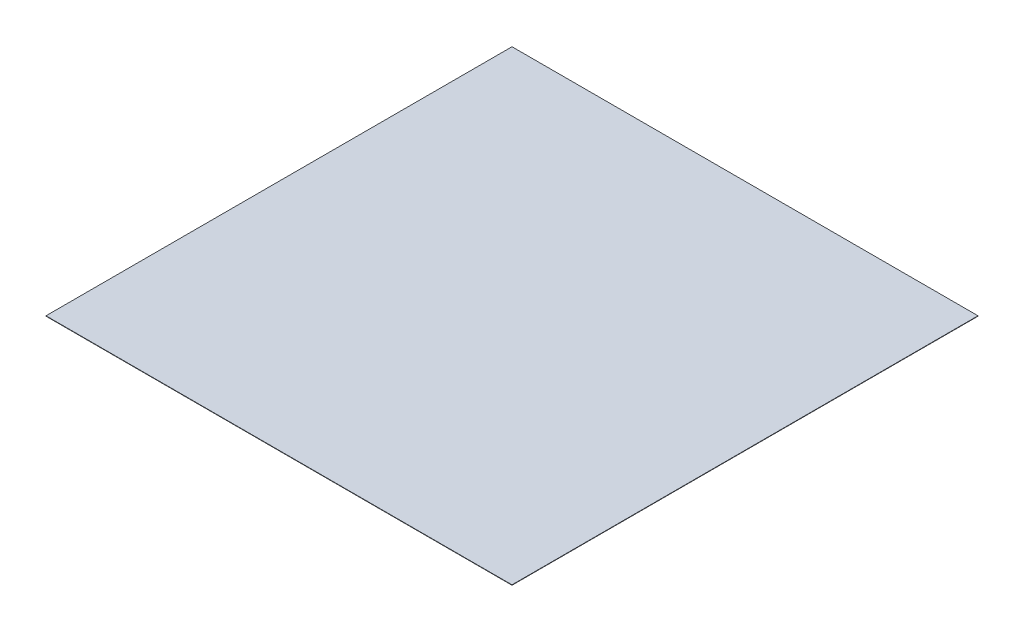
SolidWorks part; units mm, degrees
ref_plane "Front Plane" through (0, 0, 0) normal (0, 0, 1) x (1, 0, 0)
ref_plane "Top Plane" through (0, 0, 0) normal (0, 1, 0) x (1, 0, 0)
ref_plane "Right Plane" through (0, 0, 0) normal (1, 0, 0) x (0, 0, -1)
ref_plane "Plane1" through (0, 0, 134.8832) normal (0, 0, -1) x (-1, 0, 0)
sketch "Sketch2" plane through (0, 0, 134.8832) normal (0, 0, -1) x (-1, 0, 0)
  line L0 (-16.0101, 140.5644) -> (-16.0101, 106.5644)
  line L1 (-16.0101, 140.5644) -> (-16.0101, 106.5644) construction
  line L2 (-23.0101, 103.5644) -> (-19.0101, 103.5644)
  line L3 (-23.0101, 103.5644) -> (-19.0101, 103.5644) construction
  line L4 (-26.0101, 96.5644) -> (-26.0101, 100.5644)
  line L5 (-26.0101, 96.5644) -> (-26.0101, 100.5644) construction
  line L6 (-29.0101, 93.5644) -> (-63.0101, 93.5644)
  line L7 (-29.0101, 93.5644) -> (-63.0101, 93.5644) construction
  line L8 (-76.0101, 106.5644) -> (-76.0101, 140.5644)
  line L9 (-76.0101, 106.5644) -> (-76.0101, 140.5644) construction
  line L10 (-73.0101, 103.5644) -> (-69.0101, 103.5644)
  line L11 (-73.0101, 103.5644) -> (-69.0101, 103.5644) construction
  line L12 (-66.0101, 100.5644) -> (-66.0101, 96.5644)
  line L13 (-66.0101, 100.5644) -> (-66.0101, 96.5644) construction
  line L14 (-63.0101, 153.5644) -> (-29.0101, 153.5644)
  line L15 (-63.0101, 153.5644) -> (-29.0101, 153.5644) construction
  line L16 (-26.0101, 146.5644) -> (-26.0101, 150.5644)
  line L17 (-26.0101, 146.5644) -> (-26.0101, 150.5644) construction
  line L18 (-19.0101, 143.5644) -> (-23.0101, 143.5644)
  line L19 (-19.0101, 143.5644) -> (-23.0101, 143.5644) construction
  line L20 (-69.0101, 143.5644) -> (-73.0101, 143.5644)
  line L21 (-69.0101, 143.5644) -> (-73.0101, 143.5644) construction
  line L22 (-66.0101, 150.5644) -> (-66.0101, 146.5644)
  line L23 (-66.0101, 150.5644) -> (-66.0101, 146.5644) construction
  line L24 (-66.5101, 150.5644) -> (-66.5101, 146.5644)
  line L25 (-69.0101, 144.0644) -> (-73.0101, 144.0644)
  line L26 (-76.5101, 106.5644) -> (-76.5101, 140.5644)
  line L27 (-73.0101, 103.0644) -> (-69.0101, 103.0644)
  line L28 (-66.5101, 100.5644) -> (-66.5101, 96.5644)
  line L29 (-29.0101, 93.0644) -> (-63.0101, 93.0644)
  line L30 (-25.5101, 96.5644) -> (-25.5101, 100.5644)
  line L31 (-23.0101, 103.0644) -> (-19.0101, 103.0644)
  line L32 (-15.5101, 140.5644) -> (-15.5101, 106.5644)
  line L33 (-19.0101, 144.0644) -> (-23.0101, 144.0644)
  line L34 (-25.5101, 146.5644) -> (-25.5101, 150.5644)
  line L36 (-29.0101, 153.5644) -> (-84.0101, 153.5644)
  line L37 (-29.0101, 153.5644) -> (-8.0101, 153.5644)
  line L38 (-84.0101, 106.5644) -> (-84.0101, 140.5644)
  line L39 (-73.9683, 95.6063) -> (-73.9683, 95.6063)
  line L40 (-73.9683, 95.6063) -> (-73.9683, 95.6063)
  line L41 (-29.0101, 85.5644) -> (-63.0101, 85.5644)
  line L42 (-18.0519, 95.6063) -> (-18.0519, 95.6063)
  line L43 (-18.0519, 95.6063) -> (-18.0519, 95.6063)
  line L44 (-8.0101, 140.5644) -> (-8.0101, 106.5644)
  line L48 (-8.0101, 140.5644) -> (-8.0101, 153.5644)
  line L50 (-84.0101, 140.5644) -> (-84.0101, 153.5644)
  line L53 (-18.0519, 151.5226) -> (-18.0519, 151.5226) construction
  line L54 (-18.0519, 151.5226) -> (-18.0519, 151.5226) construction
  line L55 (-73.9683, 151.5226) -> (-73.9683, 151.5226) construction
  line L56 (-73.9683, 151.5226) -> (-73.9683, 151.5226) construction
  line L57 (-63.0101, 154.0644) -> (-29.0101, 154.0644) construction
  line L58 (-63.0101, 161.5644) -> (-29.0101, 161.5644) construction
  arc A0 (-19.0101, 103.5644) -> (-16.0101, 106.5644) centre (-19.0101, 106.5644) ccw
  arc A1 (-19.0101, 103.5644) -> (-16.0101, 106.5644) centre (-19.0101, 106.5644) ccw construction
  arc A2 (-23.0101, 103.5644) -> (-26.0101, 100.5644) centre (-23.0101, 100.5644) ccw
  arc A3 (-23.0101, 103.5644) -> (-26.0101, 100.5644) centre (-23.0101, 100.5644) ccw construction
  arc A4 (-29.0101, 93.5644) -> (-26.0101, 96.5644) centre (-29.0101, 96.5644) ccw
  arc A5 (-29.0101, 93.5644) -> (-26.0101, 96.5644) centre (-29.0101, 96.5644) ccw construction
  arc A6 (-66.0101, 96.5644) -> (-63.0101, 93.5644) centre (-63.0101, 96.5644) ccw
  arc A7 (-66.0101, 96.5644) -> (-63.0101, 93.5644) centre (-63.0101, 96.5644) ccw construction
  arc A8 (-76.0101, 106.5644) -> (-73.0101, 103.5644) centre (-73.0101, 106.5644) ccw
  arc A9 (-76.0101, 106.5644) -> (-73.0101, 103.5644) centre (-73.0101, 106.5644) ccw construction
  arc A10 (-66.0101, 100.5644) -> (-69.0101, 103.5644) centre (-69.0101, 100.5644) ccw
  arc A11 (-66.0101, 100.5644) -> (-69.0101, 103.5644) centre (-69.0101, 100.5644) ccw construction
  arc A12 (-26.0101, 150.5644) -> (-29.0101, 153.5644) centre (-29.0101, 150.5644) ccw
  arc A13 (-26.0101, 150.5644) -> (-29.0101, 153.5644) centre (-29.0101, 150.5644) ccw construction
  arc A14 (-26.0101, 146.5644) -> (-23.0101, 143.5644) centre (-23.0101, 146.5644) ccw
  arc A15 (-26.0101, 146.5644) -> (-23.0101, 143.5644) centre (-23.0101, 146.5644) ccw construction
  arc A16 (-16.0101, 140.5644) -> (-19.0101, 143.5644) centre (-19.0101, 140.5644) ccw
  arc A17 (-16.0101, 140.5644) -> (-19.0101, 143.5644) centre (-19.0101, 140.5644) ccw construction
  arc A18 (-63.0101, 153.5644) -> (-66.0101, 150.5644) centre (-63.0101, 150.5644) ccw
  arc A19 (-63.0101, 153.5644) -> (-66.0101, 150.5644) centre (-63.0101, 150.5644) ccw construction
  arc A20 (-69.0101, 143.5644) -> (-66.0101, 146.5644) centre (-69.0101, 146.5644) ccw
  arc A21 (-69.0101, 143.5644) -> (-66.0101, 146.5644) centre (-69.0101, 146.5644) ccw construction
  arc A22 (-73.0101, 143.5644) -> (-76.0101, 140.5644) centre (-73.0101, 140.5644) ccw
  arc A23 (-73.0101, 143.5644) -> (-76.0101, 140.5644) centre (-73.0101, 140.5644) ccw construction
  arc A24 (-69.0101, 144.0644) -> (-66.5101, 146.5644) centre (-69.0101, 146.5644) ccw
  arc A25 (-73.0101, 144.0644) -> (-76.5101, 140.5644) centre (-73.0101, 140.5644) ccw
  arc A26 (-76.5101, 106.5644) -> (-73.0101, 103.0644) centre (-73.0101, 106.5644) ccw
  arc A27 (-66.5101, 100.5644) -> (-69.0101, 103.0644) centre (-69.0101, 100.5644) ccw
  arc A28 (-66.5101, 96.5644) -> (-63.0101, 93.0644) centre (-63.0101, 96.5644) ccw
  arc A29 (-29.0101, 93.0644) -> (-25.5101, 96.5644) centre (-29.0101, 96.5644) ccw
  arc A30 (-23.0101, 103.0644) -> (-25.5101, 100.5644) centre (-23.0101, 100.5644) ccw
  arc A31 (-19.0101, 103.0644) -> (-15.5101, 106.5644) centre (-19.0101, 106.5644) ccw
  arc A32 (-15.5101, 140.5644) -> (-19.0101, 144.0644) centre (-19.0101, 140.5644) ccw
  arc A33 (-25.5101, 146.5644) -> (-23.0101, 144.0644) centre (-23.0101, 146.5644) ccw
  arc A34 (-25.5101, 150.5644) -> (-27.2073, 153.5644) centre (-29.0101, 150.5644) ccw
  arc A35 (-64.8129, 153.5644) -> (-66.5101, 150.5644) centre (-63.0101, 150.5644) ccw
  arc A37 (-63.0101, 154.0644) -> (-66.5101, 150.5644) centre (-63.0101, 150.5644) ccw construction
  arc A38 (-84.0101, 106.5644) -> (-73.9683, 95.6063) centre (-73.0101, 106.5644) ccw
  arc A39 (-73.9683, 95.6063) -> (-73.9683, 95.6063) centre (-73.9683, 95.6063) ccw
  arc A40 (-73.9683, 95.6063) -> (-63.0101, 85.5644) centre (-63.0101, 96.5644) ccw
  arc A41 (-29.0101, 85.5644) -> (-18.0519, 95.6063) centre (-29.0101, 96.5644) ccw
  arc A42 (-18.0519, 95.6063) -> (-18.0519, 95.6063) centre (-18.0519, 95.6063) ccw
  arc A43 (-18.0519, 95.6063) -> (-8.0101, 106.5644) centre (-19.0101, 106.5644) ccw
  arc A44 (-25.5101, 150.5644) -> (-29.0101, 154.0644) centre (-29.0101, 150.5644) ccw construction
  arc A49 (-8.0101, 140.5644) -> (-18.0519, 151.5226) centre (-19.0101, 140.5644) ccw construction
  arc A50 (-18.0519, 151.5226) -> (-29.0101, 161.5644) centre (-29.0101, 150.5644) ccw construction
  arc A51 (-63.0101, 161.5644) -> (-73.9683, 151.5226) centre (-63.0101, 150.5644) ccw construction
  arc A52 (-73.9683, 151.5226) -> (-84.0101, 140.5644) centre (-73.0101, 140.5644) ccw construction
  arc A53 (-18.0519, 151.5226) -> (-18.0519, 151.5226) centre (-18.0519, 151.5226) ccw construction
  arc A54 (-73.9683, 151.5226) -> (-73.9683, 151.5226) centre (-73.9683, 151.5226) ccw construction
  dimension "D1" = 0.5
  dimension "D2" = 8
extrude "Boss-Extrude1" add sketch "Sketch2" along normal blind 20 contours A41 A43 L44 L48 L37 A34 L34 A33 L33 A32 L32 A31 L31 A30 L30 A29 L29 A28 L28 A27 L27 A26 L26 A25 L25 A24 L24 A35 L36 L50 L38 A38 A40 L41
ref_plane "Plane2" through (0, 153.5644, 0) normal (0, 1, 0) x (1, 0, 0)
sketch "Sketch3" plane through (0, 153.5644, 0) normal (0, 1, 0) x (1, 0, 0)
  line L1 (-1.9899, -144.8832) -> (24.2073, -144.8832)
  line L2 (-1.9899, -144.8832) -> (-1.9899, -104.8832)
  line L3 (-1.9899, -104.8832) -> (24.2073, -104.8832)
  line L4 (98.0101, -144.8832) -> (98.0101, -104.8832)
  line L5 (67.8129, -104.8832) -> (67.8129, -144.8832)
  line L7 (24.2073, -104.8832) -> (24.2073, -144.8832)
  line L9 (48.0101, -104.8832) -> (48.0101, -144.8832) construction
  line L10 (98.0101, -124.8832) -> (-1.9899, -124.8832) construction
  line L13 (67.8129, -104.8832) -> (98.0101, -104.8832)
  line L14 (67.8129, -144.8832) -> (98.0101, -144.8832)
  circle A0 centre (93.0101, -109.8832) radius 1.5
  circle A1 centre (93.0101, -139.8832) radius 1.5
  circle A2 centre (3.0101, -139.8832) radius 1.5
  circle A3 centre (3.0101, -109.8832) radius 1.5
  dimension "D5" = 67.8129
  dimension "D1" = 3
  dimension "D2" = 3.0101
  dimension "D3" = 24.2073
  dimension "D4" = 48.0101
  dimension "D6" = 93.0101
  dimension "D7" = 98.0101
  dimension "D8" = 1.9899
  dimension "D9" = 104.8832
  dimension "D10" = 109.8832
  dimension "D11" = 124.8832
  dimension "D12" = 139.8832
extrude "Boss-Extrude2" add sketch "Sketch3" along normal blind 5 from offset 5 offset against normal yes
ref_plane "Plane3" through (0, 223.5644, 0) normal (0, 1, 0) x (1, 0, 0)
sketch "Sketch4" plane through (0, 223.5644, 0) normal (0, 1, 0) x (1, 0, 0)
  line L0 (0, 0) -> (0, 600) construction
  line L1 (600, 600) -> (-600, 600)
  line L2 (600, 600) -> (600, -600)
  line L3 (600, -600) -> (-600, -600)
  line L4 (-600, 600) -> (-600, -600)
  line L5 (0, 0) -> (600, 0) construction
  dimension "D1" = 1200
  dimension "D2" = 1200
  dimension "D3" = 600
  dimension "D4" = 600
extrude "Boss-Extrude3" add sketch "Sketch4" along normal blind 1 separate body
sketch "Sketch5" plane through (0, 153.5644, 0) normal (0, 1, 0) x (1, 0, 0)
  line L0 (98.0101, -144.8832) -> (98.0101, -104.8832) construction
  line L1 (98.0101, -104.8832) -> (67.8129, -104.8832) construction
  line L2 (67.8129, -144.8832) -> (98.0101, -144.8832) construction
  line L3 (-1.9899, -144.8832) -> (24.2073, -144.8832) construction
  line L4 (-1.9899, -104.8832) -> (-1.9899, -144.8832) construction
  line L5 (24.2073, -104.8832) -> (-1.9899, -104.8832) construction
  line L6 (98.0101, -144.8832) -> (98.0101, -104.8832)
  line L7 (98.0101, -104.8832) -> (67.8129, -104.8832)
  line L8 (67.8129, -144.8832) -> (98.0101, -144.8832)
  line L9 (-1.9899, -144.8832) -> (24.2073, -144.8832)
  line L10 (-1.9899, -104.8832) -> (-1.9899, -144.8832)
  line L11 (24.2073, -104.8832) -> (-1.9899, -104.8832)
  line L12 (24.2073, -104.8832) -> (67.8129, -104.8832)
  line L13 (24.2073, -144.8832) -> (67.8129, -144.8832)
  circle A0 centre (93.0101, -139.8832) radius 1.5 construction
  circle A1 centre (93.0101, -109.8832) radius 1.5 construction
  circle A2 centre (3.0101, -139.8832) radius 1.5 construction
  circle A3 centre (3.0101, -109.8832) radius 1.5 construction
  circle A4 centre (93.0101, -139.8832) radius 1.5
  circle A5 centre (93.0101, -109.8832) radius 1.5
  circle A6 centre (3.0101, -139.8832) radius 1.5
  circle A7 centre (3.0101, -109.8832) radius 1.5
extrude "Boss-Extrude4" add sketch "Sketch5" along normal up to surface (13.5 mm away)
